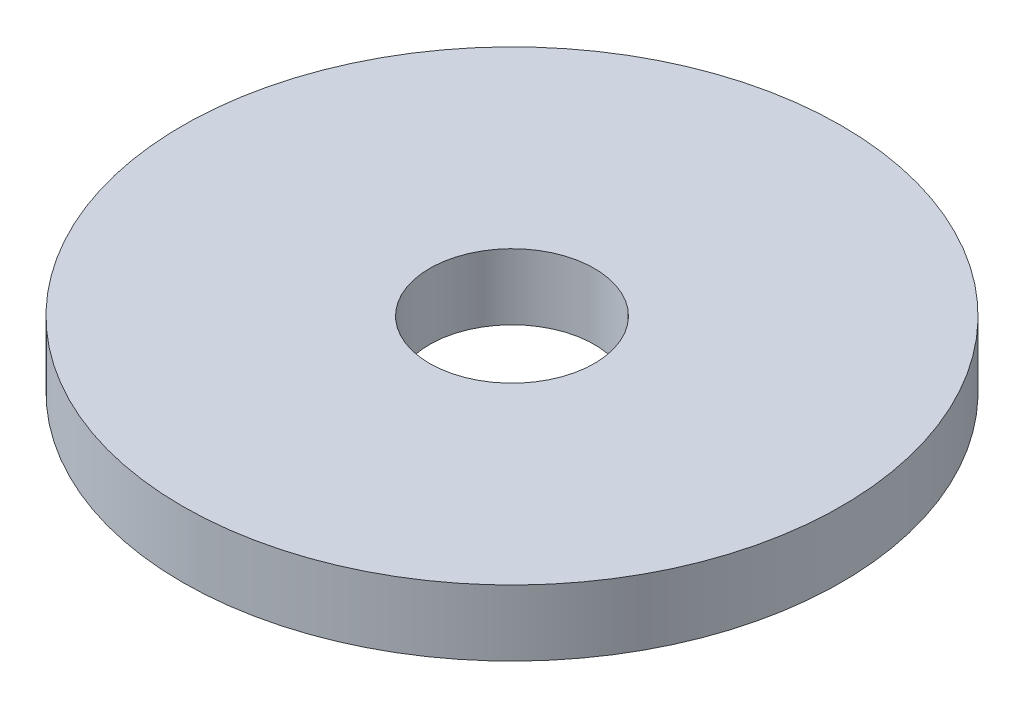
SolidWorks part; units mm, degrees
material "AISI 1020"
ref_plane "前视基准面" through (0, 0, 0) normal (0, 0, 1) x (1, 0, 0)
ref_plane "上视基准面" through (0, 0, 0) normal (0, 1, 0) x (1, 0, 0)
ref_plane "右视基准面" through (0, 0, 0) normal (1, 0, 0) x (0, 0, -1)
sketch "草图1" plane through (0, 0, 0) normal (0, 1, 0) x (1, 0, 0)
  circle A0 centre (0, 0) radius 20
  dimension "D1" = 40
extrude "凸台-拉伸1" add sketch "草图1" along normal blind 4
hole_wizard "Ø10.0 (10) 直径孔1" positions "草图3" profile "草图4" hole size "Ø10.0" standard "GB" end condition through all
sketch "草图3" plane through (0, 4, 0) normal (0, 1, 0) x (1, 0, 0)
  point P0 (0, 0)
sketch "草图4" plane through (0, 4, 0) normal (1, 0, 0) x (0, 0, 1)
  line L0 (0, 0) -> (0, 4)
  line L1 (0, 4) -> (5, 4)
  line L2 (5, 4) -> (5, 0)
  line L5 (5, 0) -> (0, 0)
  line L11 (0, -6.35) -> (0, 107.95) construction
  dimension "通孔孔直径" = 10
  dimension "通孔孔深度" = 4
